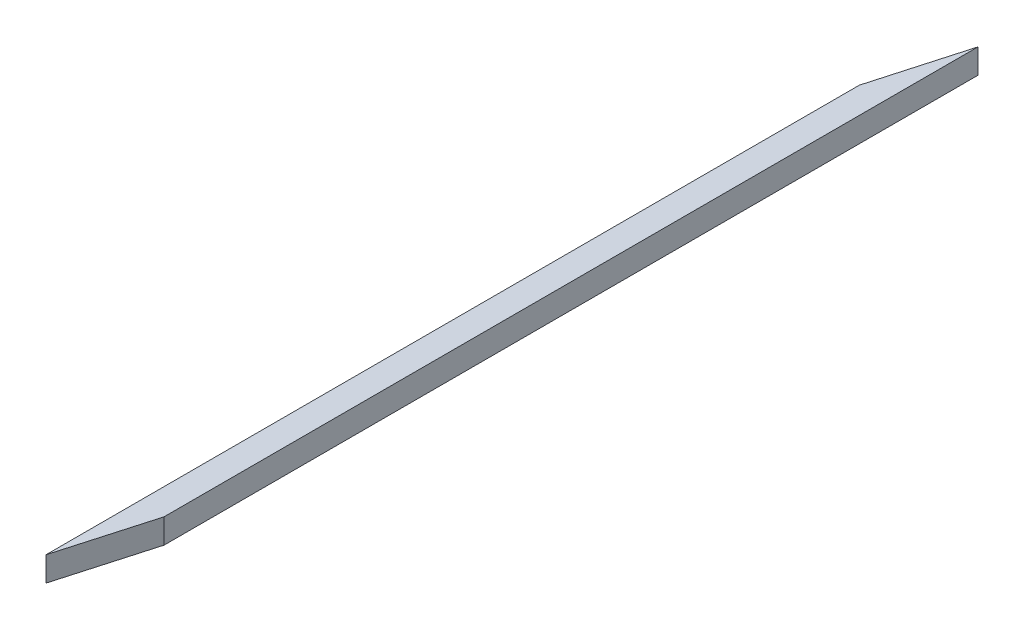
SolidWorks part; units mm, degrees
ref_plane "Front Plane" through (0, 0, 0) normal (0, 0, 1) x (1, 0, 0)
ref_plane "Top Plane" through (0, 0, 0) normal (0, 1, 0) x (1, 0, 0)
ref_plane "Right Plane" through (0, 0, 0) normal (1, 0, 0) x (0, 0, -1)
sketch "Sketch1" plane through (0, 0, 0) normal (0, 0, 1) x (1, 0, 0)
  line L1 (-48.125, 2.65) -> (1.875, 2.65)
  line L2 (-48.125, 2.65) -> (-48.125, -44.35)
  line L3 (-48.125, -44.35) -> (1.875, -44.35)
  line L4 (1.875, 2.65) -> (1.875, -44.35)
  dimension "D1" = 50
  dimension "D2" = 47
extrude "Boss-Extrude1" add sketch "Sketch1" along normal blind 1734.59
sketch "Sketch2" plane through (0, 2.65, 0) normal (0, 1, 0) x (1, 0, 0)
  line L0 (-48.125, 0) -> (-48.125, -176.7903)
  line L1 (-48.125, -1734.59) -> (-48.125, 0) construction
  line L2 (-48.125, -176.7903) -> (1.875, 0)
  line L3 (1.875, 0) -> (-48.125, 0)
  line L4 (1.875, -1734.59) -> (1.9657, -1555.6193)
  line L5 (-48.9172, -1734.3645) -> (411.5973, -116.6345) construction
  line L6 (1.9657, -1555.6193) -> (-48.9172, -1734.3645)
  line L7 (-48.9172, -1734.3645) -> (1.875, -1734.59)
extrude "Cut-Extrude1" cut sketch "Sketch2" against normal blind 50
